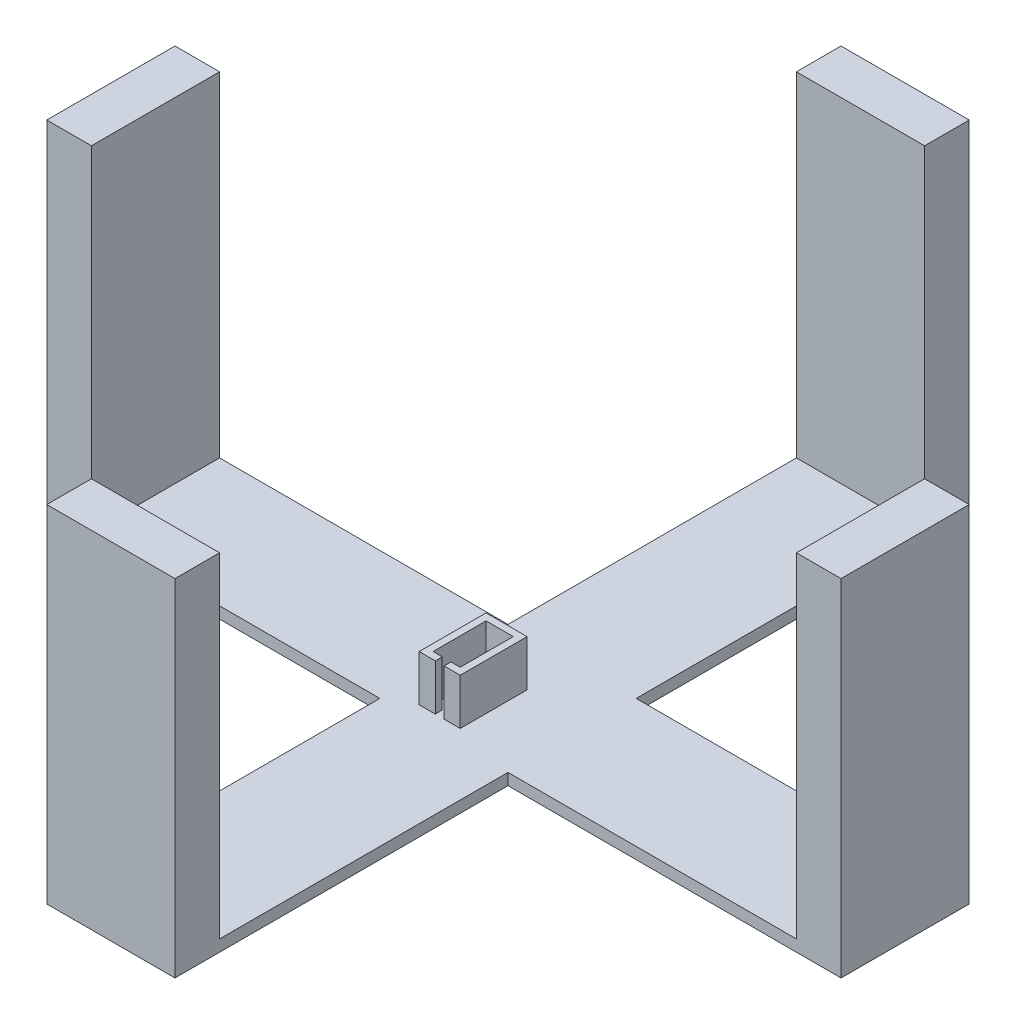
SolidWorks part; units mm, degrees
ref_plane "Front Plane" through (0, 0, 0) normal (0, 0, 1) x (1, 0, 0)
ref_plane "Top Plane" through (0, 0, 0) normal (0, 1, 0) x (1, 0, 0)
ref_plane "Right Plane" through (0, 0, 0) normal (1, 0, 0) x (0, 0, -1)
sketch "Sketch5" plane through (0, 0, 0) normal (0, 1, 0) x (1, 0, 0)
  line L3 (-27.79, 27.7908) -> (-152.8488, 27.7908)
  line L4 (-27.79, 27.7908) -> (-27.79, -27.7908)
  line L5 (-27.79, -27.7908) -> (-152.8488, -27.7908)
  line L6 (-152.8488, 27.7908) -> (-152.8488, -27.7908)
  dimension "D1" = 125.0588
  dimension "D2" = 55.5817
sketch "Sketch6" plane through (0, 0, 0) normal (0, 1, 0) x (1, 0, 0)
  circle A0 centre (0, 0) radius 27.79
extrude "Boss-Extrude3" add sketch "Sketch6" along normal mid plane 4
extrude "Boss-Extrude9" add sketch "Sketch5" along normal blind 5 separate body
pattern_circular "CirPattern7" count 4 every 90 about axis through (0, 0, 0) along (0, 1, 0) of "Boss-Extrude9"
sketch "Sketch14" plane through (0, 0, 0) normal (0, 1, 0) x (1, 0, 0)
  line L1 (-152.8488, 27.7908) -> (-172.1998, 27.7908)
  line L2 (-152.8488, 27.7908) -> (-152.8488, -27.7908)
  line L3 (-152.8488, -27.7908) -> (-172.1998, -27.7908)
  line L4 (-172.1998, 27.7908) -> (-172.1998, -27.7908)
  dimension "D1" = 19.351
  dimension "D2" = 55.5817
extrude "Boss-Extrude10" add sketch "Sketch14" along normal blind 150
pattern_circular "CirPattern9" count 4 over 360 about axis through (0, 0, 0) along (0, 1, 0) of "Boss-Extrude10"
sketch "Sketch15" plane through (0, 0, 0) normal (0, 1, 0) x (1, 0, 0)
  line L1 (-27.79, 27.79) -> (27.79, 27.79)
  line L2 (-27.79, 27.79) -> (-27.79, -27.79)
  line L3 (-27.79, -27.79) -> (27.79, -27.79)
  line L4 (27.79, 27.79) -> (27.79, -27.79)
extrude "Boss-Extrude11" add sketch "Sketch15" along normal blind 5
sketch "Sketch16" plane through (0, 0, 0) normal (0, 1, 0) x (1, 0, 0)
  line L0 (-16.8669, 7.3476) -> (0.9331, 7.3476)
  line L1 (0.9331, 7.3476) -> (0.9331, -21.6524)
  line L2 (0.9331, -21.6524) -> (-6.0669, -21.6524)
  line L3 (-6.0669, -21.6524) -> (-6.0669, -18.6524)
  line L4 (-6.0669, -18.6524) -> (-2.0669, -18.6524)
  line L5 (-2.0669, -18.6524) -> (-2.0669, 4.3476)
  line L6 (-2.0669, 4.3476) -> (-13.8669, 4.3476)
  line L7 (-13.8669, 4.3476) -> (-13.8669, -18.6524)
  line L8 (-13.8669, -18.6524) -> (-9.8669, -18.6524)
  line L9 (-9.8669, -18.6524) -> (-9.8669, -21.6524)
  line L10 (-9.8669, -21.6524) -> (-16.8669, -21.6524)
  line L11 (-16.8669, -21.6524) -> (-16.8669, 7.3476)
  dimension "D1" = 11.8
  dimension "D2" = 4
  dimension "D3" = 23
  dimension "D4" = 3
  dimension "D5" = 3
  dimension "D6" = 3
extrude "Boss-Extrude12" add sketch "Sketch16" along normal blind 25
